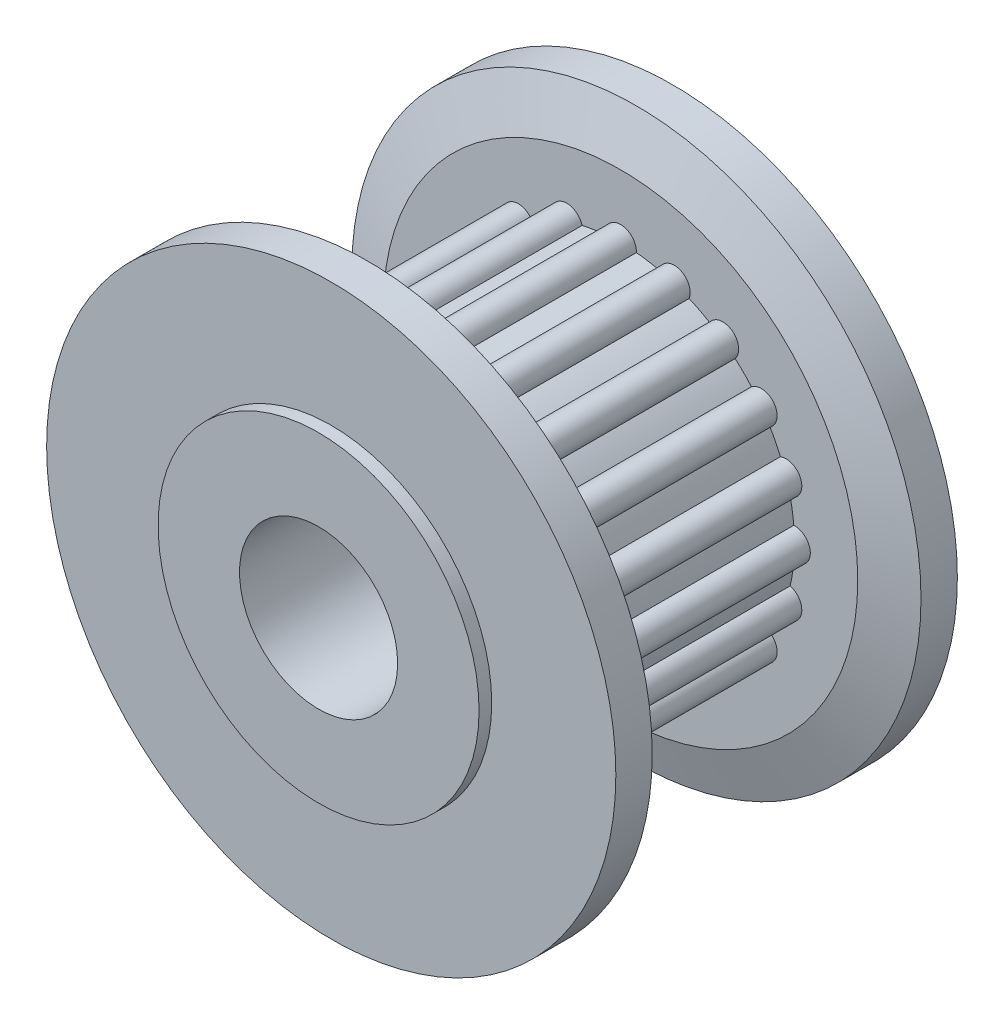
SolidWorks part; units mm, degrees
ref_plane "Front" through (0, 0, 0) normal (0, 0, 1) x (1, 0, 0)
ref_plane "Top" through (0, 0, 0) normal (0, 1, 0) x (1, 0, 0)
ref_plane "Right" through (0, 0, 0) normal (1, 0, 0) x (0, 0, -1)
sketch "Sketch1" plane through (0, 0, 0) normal (1, 0, 0) x (0, 0, -1)
  line L0 (0, 0) -> (16.6784, 0) construction
  line L1 (50, 0) -> (-50, 0) construction
  line L2 (0, 0) -> (0, 25.6646) construction
  line L3 (-3.75, 7.5) -> (-3.75, 5.5)
  line L4 (-3.75, 5.5) -> (3.75, 5.5)
  line L5 (3.75, 5.5) -> (3.75, 7.5)
  line L6 (4.25, 9) -> (5.4, 9)
  line L7 (5.4, 9) -> (5.4, 5.075)
  line L8 (5.8, 2.5) -> (-5.8, 2.5)
  line L9 (-5.4, 5.075) -> (-5.8, 5.075)
  line L10 (-5.4, 9) -> (-4.25, 9)
  line L11 (-4.25, 9) -> (-3.75, 7.5)
  line L12 (4.25, 9) -> (3.75, 7.5)
  line L13 (-5.4, 9) -> (-5.4, 5.075)
  line L14 (-5.8, 5.075) -> (-5.8, 2.5)
  line L15 (5.4, 5.075) -> (5.8, 5.075)
  line L16 (5.8, 5.075) -> (5.8, 2.5)
  point P12 (0, 0)
  dimension "D1" = 18
  dimension "D2" = 5
  dimension "D3" = 7.5
  dimension "D4" = 0.4
  dimension "D5" = 10.15
  dimension "D6" = 11
  dimension "D7" = 1.5
  dimension "D8" = 0.5
  dimension "D9" = 11.6
revolve "Revolve1" add sketch "Sketch1" angle 360 about L0
sketch "Sketch2" plane through (0, 0, -3.75) normal (0, 0, 1) x (1, 0, 0)
  circle A0 centre (0, 0) radius 5.5 construction
  arc A1 (-0.4995, 5.4773) -> (0.4995, 5.4773) centre (0, 5.5) cw
  arc A2 (-0.4995, 5.4773) -> (0.4995, 5.4773) centre (0, 0) cw
  circle M1 centre (0, 0) radius 5.5
  dimension "D1" = 11
  dimension "D2" = 0.5
extrude "Boss-Extrude1" add sketch "Sketch2" along normal up to surface (7.5 mm away) contours A1 M1 up to face at (7.5, 0, 3.75)
pattern_circular "CirPattern1" count 20 over 360 about axis through (0, 0, 0) along (0, 0, 1) of "Boss-Extrude1"
